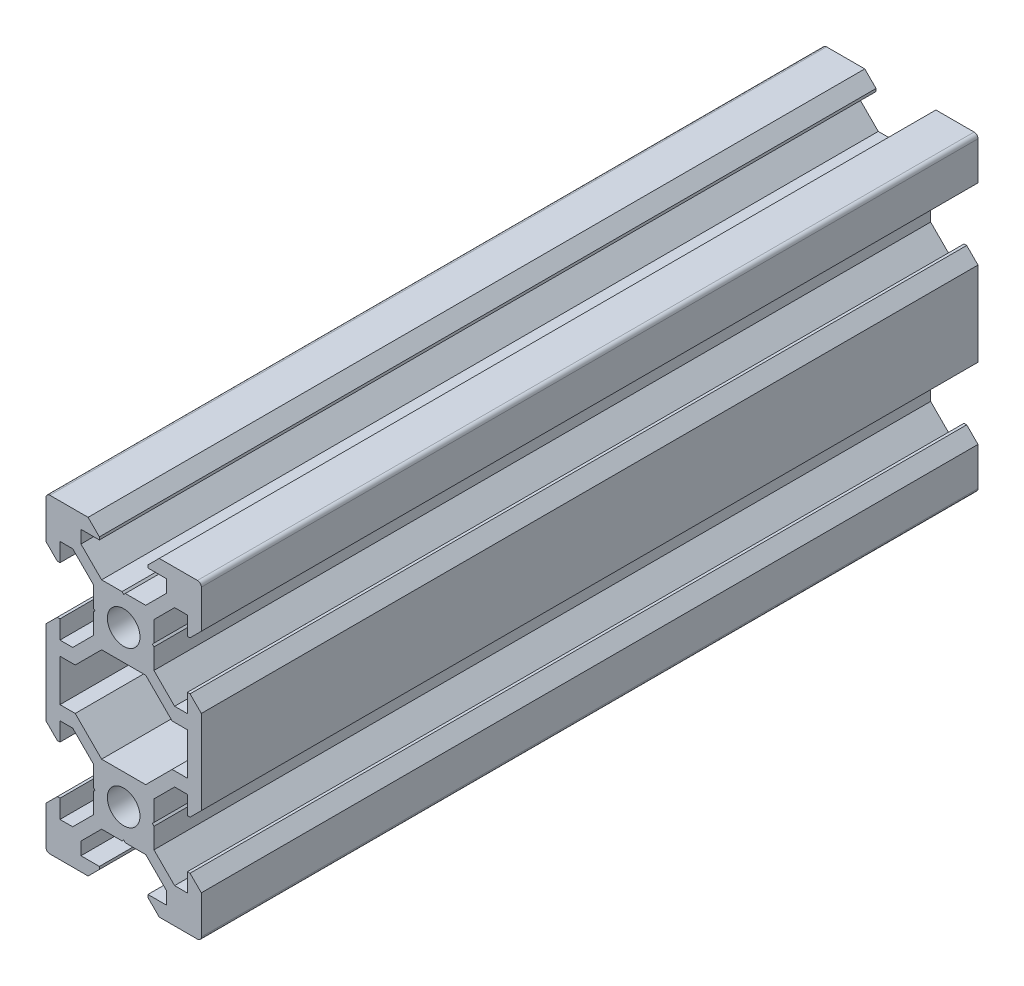
SolidWorks part; units mm, degrees
material "6061-T6 (SS)"
ref_plane "Front Plane" through (0, 0, 0) normal (0, 0, 1) x (1, 0, 0)
ref_plane "Top Plane" through (0, 0, 0) normal (0, 1, 0) x (1, 0, 0)
ref_plane "Right Plane" through (0, 0, 0) normal (1, 0, 0) x (0, 0, -1)
sketch "Sketch1" plane through (0, 0, 0) normal (0, 0, 1) x (1, 0, 0)
  line L0 (0, 0) -> (10, 0) construction
  line L1 (9.5, -20) -> (-9.5, -20)
  line L2 (10, -19.5) -> (10, 19.5)
  line L3 (9.5, 20) -> (-9.5, 20)
  line L4 (-10, -19.5) -> (-10, 19.5)
  line L5 (10, -20) -> (-10, 20) construction
  line L6 (10, 20) -> (-10, -20) construction
  circle A0 centre (0, 10) radius 2.1
  circle A1 centre (0, -10) radius 2.1
  arc A2 (-9.5, -20) -> (-10, -19.5) centre (-9.5, -19.5) cw
  arc A3 (9.5, -20) -> (10, -19.5) centre (9.5, -19.5) ccw
  arc A4 (10, 19.5) -> (9.5, 20) centre (9.5, 19.5) ccw
  arc A5 (-9.5, 20) -> (-10, 19.5) centre (-9.5, 19.5) ccw
  point P0 (0, 0)
  line B0 (0, 10) -> (0, 20) construction
  line B1 (0, 13.69) -> (-0.21, 13.9)
  line B2 (-0.21, 13.9) -> (-2.8393, 13.9)
  line B3 (-2.8393, 13.9) -> (-5.5, 16.5607)
  line B4 (-5.5, 16.5607) -> (-5.5, 18.2)
  line B5 (-5.5, 18.2) -> (-3.125, 18.2)
  line B6 (-3.125, 18.2) -> (-3.125, 18.545)
  line B7 (-3.125, 18.545) -> (-4.58, 20)
  line B8 (-4.58, 20) -> (4.58, 20)
  line B9 (0, 10) -> (-5.9132, 15.9132) construction
  line B10 (3.125, 18.545) -> (4.58, 20)
  line B11 (3.125, 18.2) -> (3.125, 18.545)
  line B12 (5.5, 18.2) -> (3.125, 18.2)
  line B13 (5.5, 16.5607) -> (5.5, 18.2)
  line B14 (2.8393, 13.9) -> (5.5, 16.5607)
  line B15 (0.21, 13.9) -> (2.8393, 13.9)
  line B16 (0, 13.69) -> (0.21, 13.9)
  line B17 (0, 10) -> (-10, 10) construction
  line B18 (-3.69, 10) -> (-3.9, 9.79)
  line B19 (-3.9, 9.79) -> (-3.9, 7.1607)
  line B20 (-3.9, 7.1607) -> (-6.5607, 4.5)
  line B21 (-6.5607, 4.5) -> (-8.2, 4.5)
  line B22 (-8.2, 4.5) -> (-8.2, 6.875)
  line B23 (-8.2, 6.875) -> (-8.545, 6.875)
  line B24 (-8.545, 6.875) -> (-10, 5.42)
  line B25 (-10, 5.42) -> (-10, 14.58)
  line B26 (0, 10) -> (-5.9132, 4.0868) construction
  line B27 (-8.545, 13.125) -> (-10, 14.58)
  line B28 (-8.2, 13.125) -> (-8.545, 13.125)
  line B29 (-8.2, 15.5) -> (-8.2, 13.125)
  line B30 (-6.5607, 15.5) -> (-8.2, 15.5)
  line B31 (-3.9, 12.8393) -> (-6.5607, 15.5)
  line B32 (-3.9, 10.21) -> (-3.9, 12.8393)
  line B33 (-3.69, 10) -> (-3.9, 10.21)
  line B34 (0, -10) -> (-10, -10) construction
  line B35 (-3.69, -10) -> (-3.9, -10.21)
  line B36 (-3.9, -10.21) -> (-3.9, -12.8393)
  line B37 (-3.9, -12.8393) -> (-6.5607, -15.5)
  line B38 (-6.5607, -15.5) -> (-8.2, -15.5)
  line B39 (-8.2, -15.5) -> (-8.2, -13.125)
  line B40 (-8.2, -13.125) -> (-8.545, -13.125)
  line B41 (-8.545, -13.125) -> (-10, -14.58)
  line B42 (-10, -14.58) -> (-10, -5.42)
  line B43 (0, -10) -> (-5.9132, -15.9132) construction
  line B44 (-8.545, -6.875) -> (-10, -5.42)
  line B45 (-8.2, -6.875) -> (-8.545, -6.875)
  line B46 (-8.2, -4.5) -> (-8.2, -6.875)
  line B47 (-6.5607, -4.5) -> (-8.2, -4.5)
  line B48 (-3.9, -7.1607) -> (-6.5607, -4.5)
  line B49 (-3.9, -9.79) -> (-3.9, -7.1607)
  line B50 (-3.69, -10) -> (-3.9, -9.79)
  line B51 (0, -10) -> (0, -20) construction
  line B52 (0, -13.69) -> (0.21, -13.9)
  line B53 (0.21, -13.9) -> (2.8393, -13.9)
  line B54 (2.8393, -13.9) -> (5.5, -16.5607)
  line B55 (5.5, -16.5607) -> (5.5, -18.2)
  line B56 (5.5, -18.2) -> (3.125, -18.2)
  line B57 (3.125, -18.2) -> (3.125, -18.545)
  line B58 (3.125, -18.545) -> (4.58, -20)
  line B59 (4.58, -20) -> (-4.58, -20)
  line B60 (0, -10) -> (5.9132, -15.9132) construction
  line B61 (-3.125, -18.545) -> (-4.58, -20)
  line B62 (-3.125, -18.2) -> (-3.125, -18.545)
  line B63 (-5.5, -18.2) -> (-3.125, -18.2)
  line B64 (-5.5, -16.5607) -> (-5.5, -18.2)
  line B65 (-2.8393, -13.9) -> (-5.5, -16.5607)
  line B66 (-0.21, -13.9) -> (-2.8393, -13.9)
  line B67 (0, -13.69) -> (-0.21, -13.9)
  line B68 (0, -10) -> (10, -10) construction
  line B69 (3.69, -10) -> (3.9, -9.79)
  line B70 (3.9, -9.79) -> (3.9, -7.1607)
  line B71 (3.9, -7.1607) -> (6.5607, -4.5)
  line B72 (6.5607, -4.5) -> (8.2, -4.5)
  line B73 (8.2, -4.5) -> (8.2, -6.875)
  line B74 (8.2, -6.875) -> (8.545, -6.875)
  line B75 (8.545, -6.875) -> (10, -5.42)
  line B76 (10, -5.42) -> (10, -14.58)
  line B77 (0, -10) -> (5.9132, -4.0868) construction
  line B78 (8.545, -13.125) -> (10, -14.58)
  line B79 (8.2, -13.125) -> (8.545, -13.125)
  line B80 (8.2, -15.5) -> (8.2, -13.125)
  line B81 (6.5607, -15.5) -> (8.2, -15.5)
  line B82 (3.9, -12.8393) -> (6.5607, -15.5)
  line B83 (3.9, -10.21) -> (3.9, -12.8393)
  line B84 (3.69, -10) -> (3.9, -10.21)
  line B85 (0, 10) -> (10, 10) construction
  line B86 (3.69, 10) -> (3.9, 10.21)
  line B87 (3.9, 10.21) -> (3.9, 12.8393)
  line B88 (3.9, 12.8393) -> (6.5607, 15.5)
  line B89 (6.5607, 15.5) -> (8.2, 15.5)
  line B90 (8.2, 15.5) -> (8.2, 13.125)
  line B91 (8.2, 13.125) -> (8.545, 13.125)
  line B92 (8.545, 13.125) -> (10, 14.58)
  line B93 (10, 14.58) -> (10, 5.42)
  line B94 (0, 10) -> (5.9132, 15.9132) construction
  line B95 (8.545, 6.875) -> (10, 5.42)
  line B96 (8.2, 6.875) -> (8.545, 6.875)
  line B97 (8.2, 4.5) -> (8.2, 6.875)
  line B98 (6.5607, 4.5) -> (8.2, 4.5)
  line B99 (3.9, 7.1607) -> (6.5607, 4.5)
  line B100 (3.9, 9.79) -> (3.9, 7.1607)
  line B101 (3.69, 10) -> (3.9, 9.79)
  line B102 (-8.2, -2.7) -> (-8.2, 2.7)
  line B103 (-8.2, 2.7) -> (-6.2393, 2.7)
  line B104 (-6.2393, 2.7) -> (-2.8393, 6.1)
  line B105 (-2.8393, 6.1) -> (2.8393, 6.1)
  line B106 (0, 6.1) -> (0, 0) construction
  line B107 (0, 0) -> (-8.2, 0) construction
  line B108 (6.2393, 2.7) -> (2.8393, 6.1)
  line B109 (8.2, 2.7) -> (6.2393, 2.7)
  line B110 (8.2, -2.7) -> (8.2, 2.7)
  line B111 (8.2, -2.7) -> (6.2393, -2.7)
  line B112 (6.2393, -2.7) -> (2.8393, -6.1)
  line B113 (-2.8393, -6.1) -> (2.8393, -6.1)
  line B114 (-6.2393, -2.7) -> (-2.8393, -6.1)
  line B115 (-8.2, -2.7) -> (-6.2393, -2.7)
  line B116 (0, 6.1) -> (0, 10) construction
  line B117 (0, 10) -> (-5.0927, 4.9073) construction
  dimension "D4" = 4.2
  dimension "D5" = 0.5
  dimension "D1" = 20
  dimension "D2" = 40
  dimension "D3" = 20
sketch_block_instance "V Slot 1-4"
sketch_block "V Slot 1" parameters "D1"=10, "D2"=11, "D3"=4.3, "D4"=1.8, "D5"=0.21, "D6"=45, "D7"=9.16, "D8"=1.5, "D9"=6.25
sketch_block_instance "V Slot 1-5"
sketch_block_instance "V Slot 1-6"
sketch_block_instance "V Slot 1-7"
sketch_block_instance "V Slot 1-8"
sketch_block_instance "V Slot 1-9"
sketch_block_instance "Center Cutout 1-1"
sketch_block "Center Cutout 1" parameters "D1"=5.4, "D2"=12.2, "D3"=8.2, "D4"=45, "D5"=10, "D6"=1.5
extrude "Boss-Extrude1" add sketch "Sketch1" along normal blind 100 contours B101 B86 B87 B88 B89 B90 B91 B92 L2 A4 L3 B10 B11 B12 B13 B14 B15 B16 B1 B2 B3 B4 B5 B6 B7 A5 L4 B27 B28 B29 B30 B31 B32 B33 B18 B19 B20 B21 B22 B23 B24 B44 B45 B46 B47 B48 B49 B50 B35
